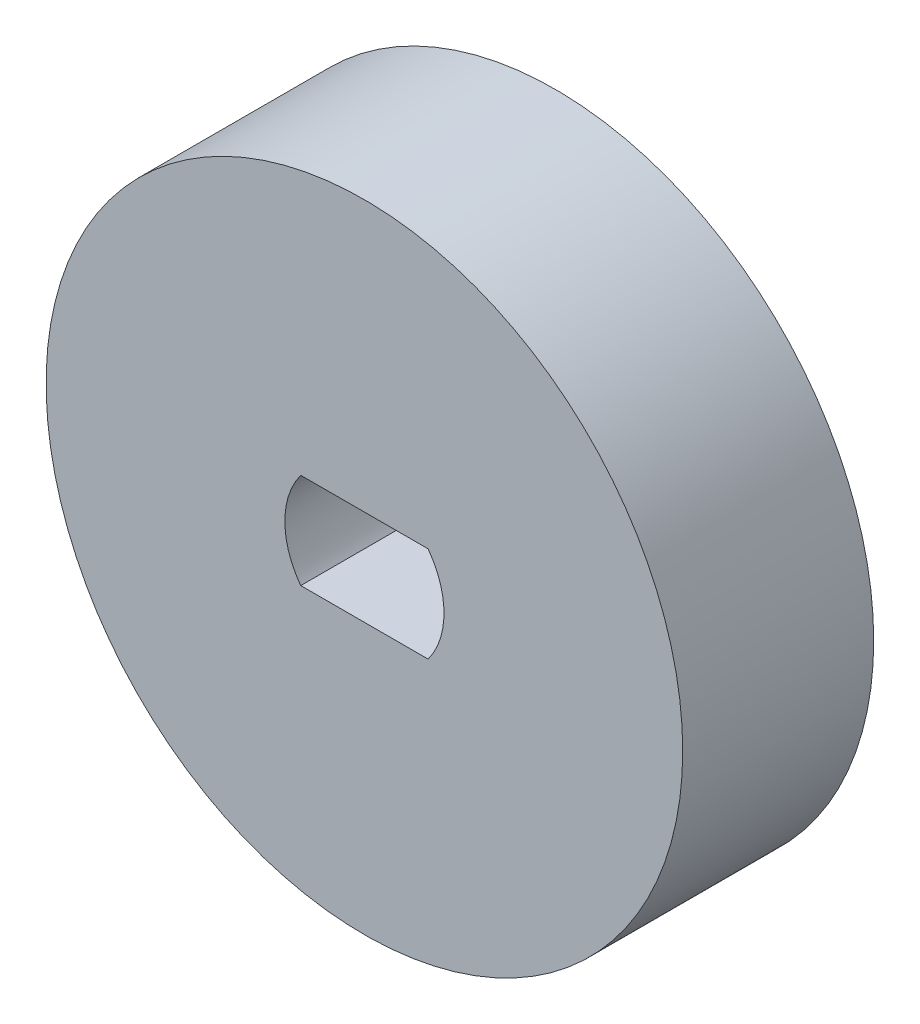
SolidWorks part; units mm, degrees
ref_plane "Front Plane" through (0, 0, 0) normal (0, 0, 1) x (1, 0, 0)
ref_plane "Top Plane" through (0, 0, 0) normal (0, 1, 0) x (1, 0, 0)
ref_plane "Right Plane" through (0, 0, 0) normal (1, 0, 0) x (0, 0, -1)
sketch "Sketch1" plane through (0, 0, 0) normal (0, 0, 1) x (-1, 0, 0)
  line L0 (-10.5062, 1.5) -> (-6.5062, 1.5)
  line L1 (-10.5062, -1.5) -> (-6.5062, -1.5)
  line L2 (-9.9683, 1.5) -> (-9.9683, -1.5) construction
  circle A0 centre (-8.5062, 0) radius 10
  circle A2 centre (-8.5062, 0) radius 2.5
  point P9 (-9.9683, 0)
extrude "Boss-Extrude1" add sketch "Sketch1" along normal blind 6 contours A0 A2 | L1 A2 | L0 A2
